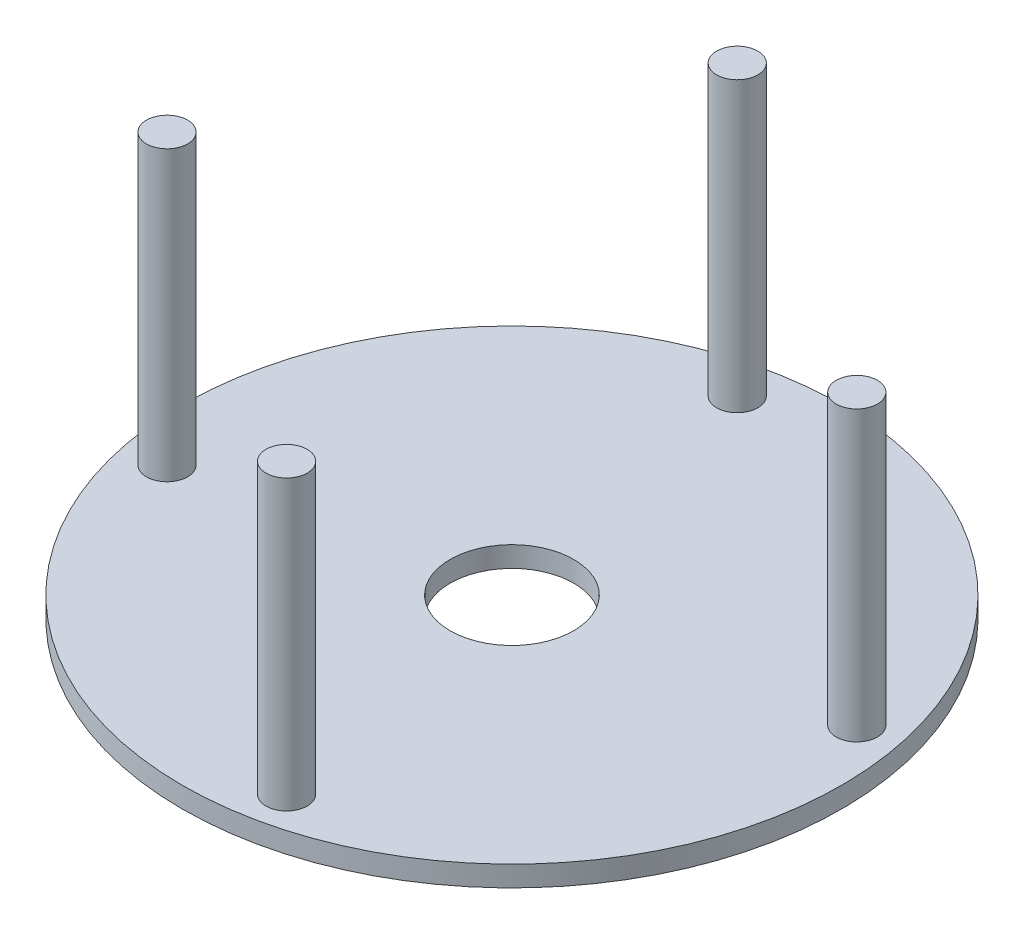
SolidWorks part; units mm, degrees
ref_plane "Front Plane" through (0, 0, 0) normal (0, 0, 1) x (1, 0, 0)
ref_plane "Top Plane" through (0, 0, 0) normal (0, 1, 0) x (1, 0, 0)
ref_plane "Right Plane" through (0, 0, 0) normal (1, 0, 0) x (0, 0, -1)
sketch "Sketch1" plane through (0, 0, 0) normal (0, 1, 0) x (1, 0, 0)
  circle A0 centre (0, 0) radius 50.8
  circle A1 centre (0, 0) radius 9.525
  dimension "D1" = 101.6
  dimension "D2" = 19.05
extrude "Boss-Extrude1" add sketch "Sketch1" along normal blind 3.175 contours A1 | A0
sketch "Sketch2" plane through (0, 3.175, 0) normal (0, 1, 0) x (1, 0, 0)
  circle A0 centre (-9.2146, 43.9456) radius 3.175
  circle A1 centre (0, 0) radius 146.05
  circle A2 centre (0, 0) radius 146.05
  circle A3 centre (0, 0) radius 146.05
  circle A4 centre (0, 0) radius 146.05
  circle A5 centre (43.9456, 9.2146) radius 3.175
  circle A6 centre (9.2146, -43.9456) radius 3.175
  circle A7 centre (-43.9456, -9.2146) radius 3.175
  dimension "D3" = 6.35
  dimension "D4" = 6.35
  dimension "D5" = 6.35
  dimension "D6" = 6.35
  dimension "D1" = 0
  dimension "D2" = 0
extrude "Boss-Extrude2" add sketch "Sketch2" along normal blind 44.45 contours A0 | A5 | A6 | A7
equation "\"D4@Sketch2\"=\"D3@Sketch2\""
equation "\"D5@Sketch2\"=\"D3@Sketch2\""
equation "\"D6@Sketch2\"=\"D3@Sketch2\""
